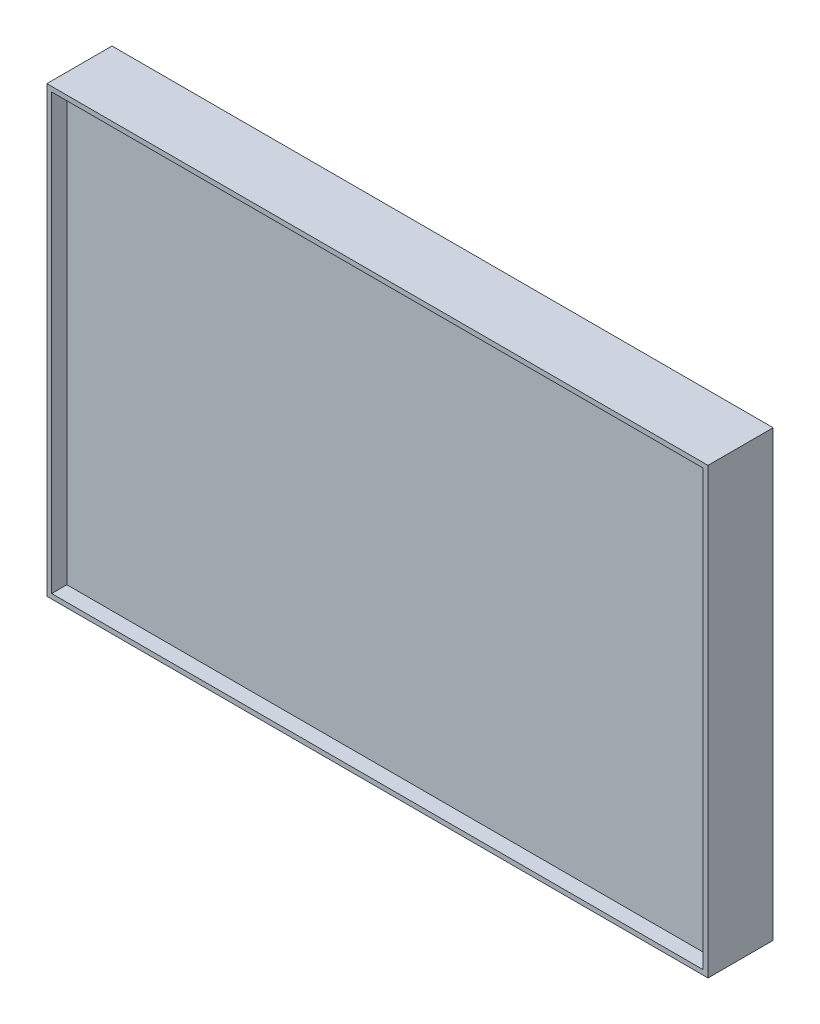
SolidWorks part; units mm, degrees
ref_plane "Plan de face" through (0, 0, 0) normal (0, 0, 1) x (1, 0, 0)
ref_plane "Plan de dessus" through (0, 0, 0) normal (0, 1, 0) x (1, 0, 0)
ref_plane "Plan de droite" through (0, 0, 0) normal (1, 0, 0) x (0, 0, -1)
sketch "Esquisse1" plane through (0, 0, 0) normal (0, 0, 1) x (1, 0, 0)
  line L1 (-3241.2789, 1394.3401) -> (-197.2789, 1394.3401)
  line L2 (-3241.2789, 1394.3401) -> (-3241.2789, -649.6599)
  line L3 (-3241.2789, -649.6599) -> (-197.2789, -649.6599)
  line L4 (-197.2789, 1394.3401) -> (-197.2789, -649.6599)
  dimension "D1" = 2044
  dimension "D2" = 3044
extrude "Boss.-Extru.1" add sketch "Esquisse1" along normal blind 300
sketch "Esquisse2" plane through (0, 0, 300) normal (0, 0, 1) x (1, 0, 0)
  line L0 (-3241.2789, 1394.3401) -> (-3241.2789, -649.6599) construction
  line L1 (-3219.2789, 1372.3401) -> (-219.2789, 1372.3401)
  line L2 (-3219.2789, 1372.3401) -> (-3219.2789, -627.6599)
  line L3 (-3219.2789, -627.6599) -> (-219.2789, -627.6599)
  line L4 (-219.2789, 1372.3401) -> (-219.2789, -627.6599)
  line L5 (-3241.2789, -649.6599) -> (-197.2789, -649.6599) construction
  dimension "D1" = 2000
  dimension "D2" = 3000
  dimension "D3" = 22
  dimension "D4" = 22
extrude "Enlèv. mat.-Extru.2" cut sketch "Esquisse2" against normal blind 70
